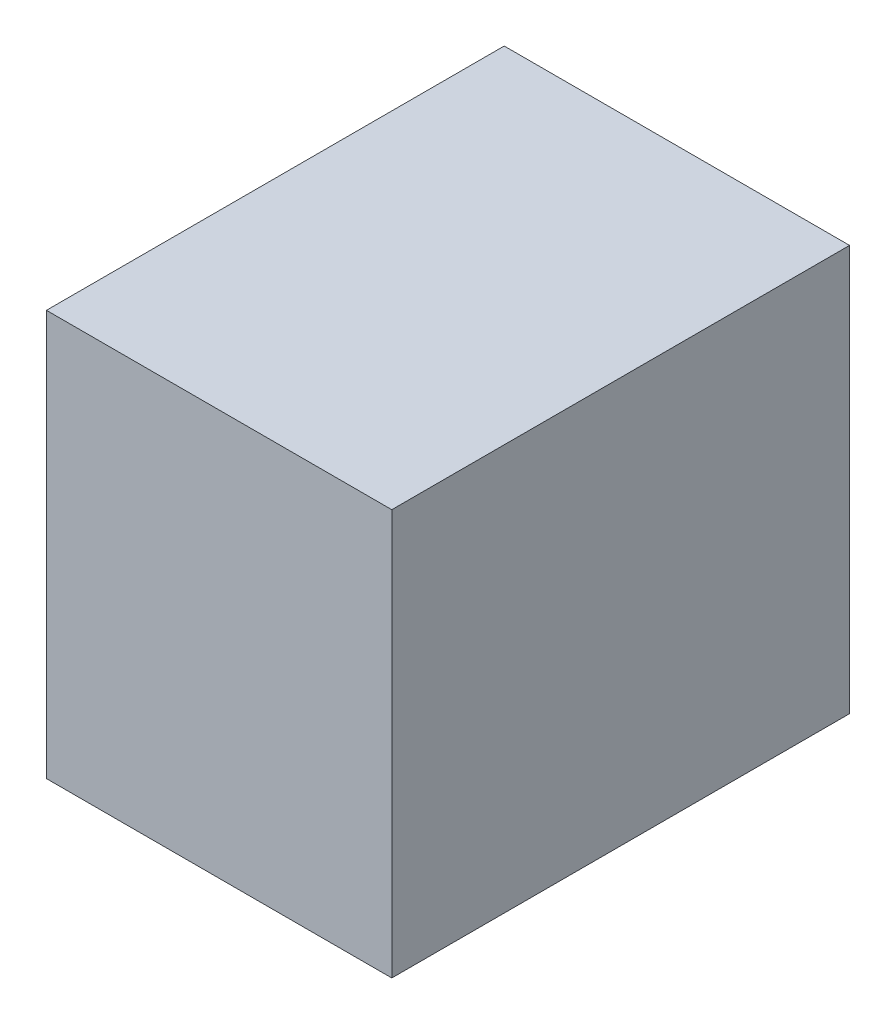
SolidWorks part; units mm, degrees
ref_plane "Front Plane" through (0, 0, 0) normal (0, 0, 1) x (1, 0, 0)
ref_plane "Top Plane" through (0, 0, 0) normal (0, 1, 0) x (1, 0, 0)
ref_plane "Right Plane" through (0, 0, 0) normal (1, 0, 0) x (0, 0, -1)
sketch "Sketch1" plane through (0, 0, 0) normal (0, 0, 1) x (1, 0, 0)
  line L0 (-12.3404, -6.9967) -> (-12.3404, 8.5033)
  line L1 (-12.3404, 8.5033) -> (-15.3404, 8.5033)
  line L2 (-15.3404, 8.5033) -> (-15.3404, -9.9967)
  line L3 (-15.3404, -9.9967) -> (6.1596, -9.9967)
  line L4 (6.1596, -9.9967) -> (6.1596, 15.2533)
  line L5 (6.1596, 15.2533) -> (-15.3404, 15.2533)
  line L6 (-15.3404, 15.2533) -> (-15.3404, 12.2533)
  line L7 (-15.3404, 12.2533) -> (3.1596, 12.2533)
  line L8 (3.1596, 12.2533) -> (3.1596, -6.9967)
  line L9 (3.1596, -6.9967) -> (-12.3404, -6.9967)
  dimension "D1" = 3
  dimension "D2" = 3
  dimension "D3" = 3
  dimension "D4" = 3
  dimension "D5" = 18.5
  dimension "D6" = 15.5
  dimension "D7" = 15.5
  dimension "D8" = 19.25
extrude "Boss-Extrude1" add sketch "Sketch1" along normal blind 25.5
sketch "Sketch2" plane through (0, 0, 25.5) normal (0, 0, 1) x (1, 0, 0)
  line L0 (-15.3404, 15.2533) -> (6.1596, 15.2533)
  line L1 (6.1596, 15.2533) -> (6.1596, -9.9967)
  line L2 (6.1596, -9.9967) -> (-15.3404, -9.9967)
  line L3 (-15.3404, -9.9967) -> (-15.3404, 15.2533)
extrude "Boss-Extrude2" add sketch "Sketch2" along normal blind 3
